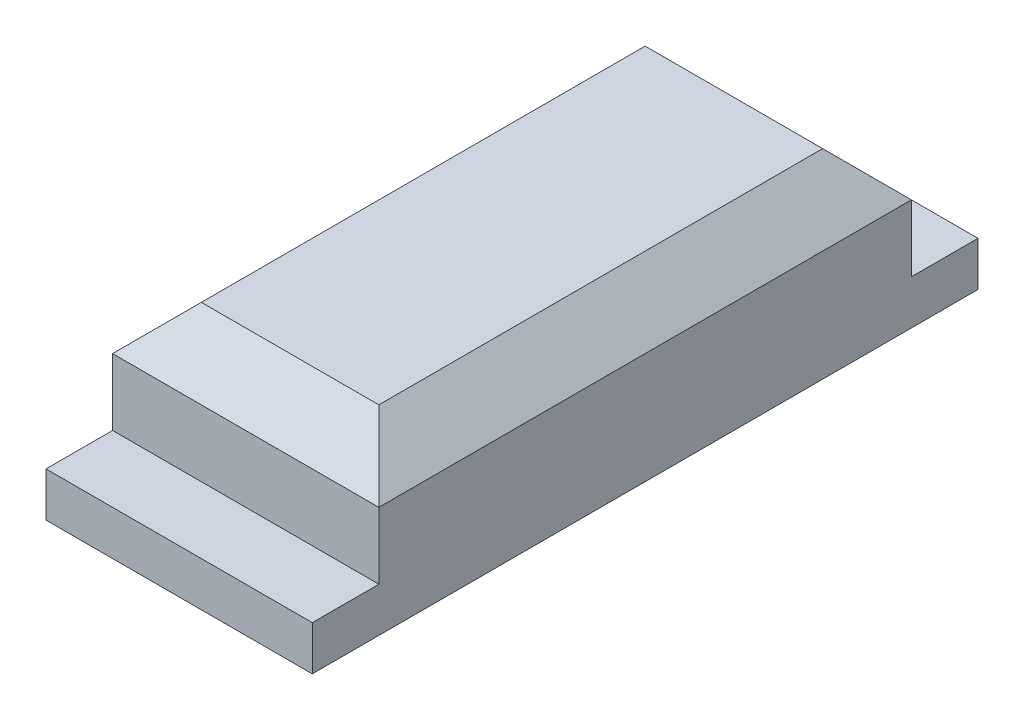
SolidWorks part; units mm, degrees
ref_plane "Front Plane" through (0, 0, 0) normal (0, 0, 1) x (1, 0, 0)
ref_plane "Top Plane" through (0, 0, 0) normal (0, 1, 0) x (1, 0, 0)
ref_plane "Right Plane" through (0, 0, 0) normal (1, 0, 0) x (0, 0, -1)
sketch "Sketch1" plane through (0, 0, 0) normal (0, 1, 0) x (1, 0, 0)
  line L1 (0, 0) -> (12, 0)
  line L2 (0, 0) -> (0, 30)
  line L3 (0, 30) -> (12, 30)
  line L4 (12, 0) -> (12, 30)
  dimension "D1" = 30
  dimension "D2" = 12
extrude "Boss-Extrude1" add sketch "Sketch1" along normal blind 2
sketch "Sketch2" plane through (0, 2, 0) normal (0, 1, 0) x (1, 0, 0)
  line L0 (0, 30) -> (0, 0) construction
  line L1 (0, 27) -> (12, 27)
  line L2 (0, 27) -> (0, 3)
  line L3 (0, 3) -> (12, 3)
  line L4 (12, 27) -> (12, 3)
  line L5 (12, 0) -> (12, 30) construction
  line L6 (12, 30) -> (0, 30) construction
  line L7 (0, 0) -> (12, 0) construction
  dimension "D1" = 3
  dimension "D2" = 3
  dimension "D3" = 24
extrude "Boss-Extrude2" add sketch "Sketch2" along normal blind 5
chamfer "Chamfer1" distance 2 angle 45 4 edges at (6, 7, -27) (12, 7, -15) (6, 7, -3) (0, 7, -15)
